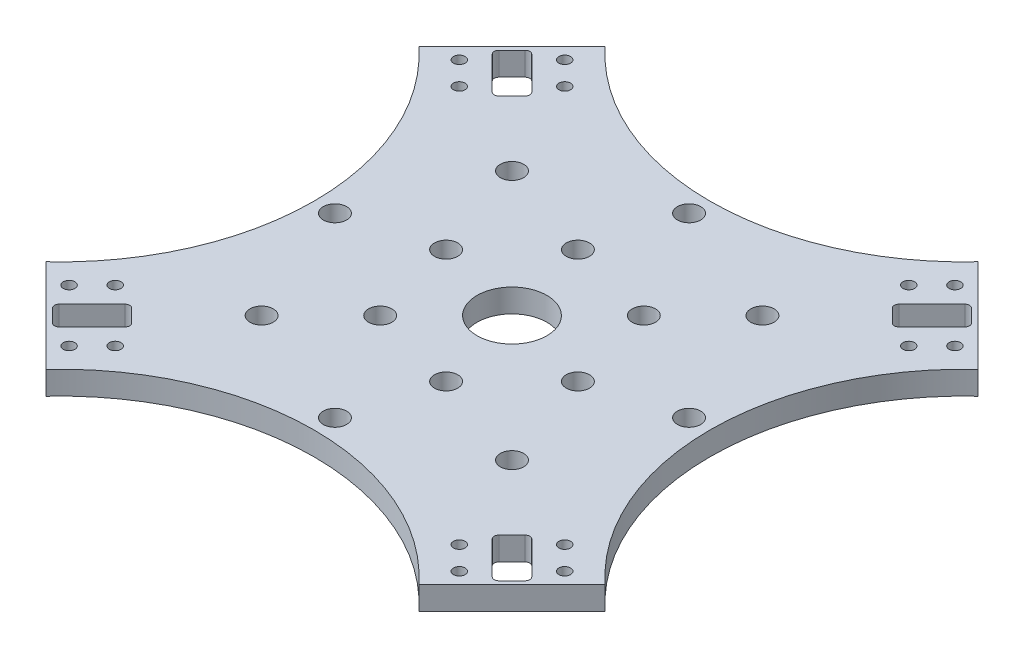
SolidWorks part; units mm, degrees
ref_plane "Front Plane" through (0, 0, 0) normal (0, 0, 1) x (1, 0, 0)
ref_plane "Top Plane" through (0, 0, 0) normal (0, 1, 0) x (1, 0, 0)
ref_plane "Right Plane" through (0, 0, 0) normal (1, 0, 0) x (0, 0, -1)
sketch "Sketch3" plane through (0, 0, 0) normal (0, 1, 0) x (1, 0, 0)
  line L0 (-60, 40) -> (-40, 60)
  line L5 (-60, 60) -> (-50, 50) construction
  line L6 (-60, -60) -> (-50, -50) construction
  line L7 (40, 60) -> (60, 40)
  line L8 (40, -60) -> (60, -40)
  line L9 (-60, -40) -> (-40, -60)
  line L10 (50, 50) -> (60, 60) construction
  line L11 (50, -50) -> (60, -60) construction
  arc A0 (-40, 60) -> (40, 60) centre (0, 96.9643) ccw
  arc A1 (-40, -60) -> (40, -60) centre (0, -96.9643) cw
  arc A2 (-60, -40) -> (-60, 40) centre (-96.9643, 0) ccw
  arc A3 (60, -40) -> (60, 40) centre (96.9643, 0) cw
  point P0 (0, 0)
  point P18 (0, 42.5)
  point P19 (-42.5, 0)
  point P20 (0, -42.5)
  point P21 (42.5, 0)
  dimension "D1" = 120
  dimension "D2" = 120
  dimension "D3" = 17.5
  dimension "D4" = 2.5
  dimension "D5" = 17.5
  dimension "D6" = 17.5
extrude "Boss-Extrude1" add sketch "Sketch3" along normal blind 5
ref_plane "Plane1" through (0, 5, 0) normal (0, 1, 0) x (1, 0, 0)
sketch "Sketch7" plane through (0, 5, 0) normal (0, 1, 0) x (1, 0, 0)
  line L0 (-50, 50) -> (50, -50)
  line L1 (-40, 60) -> (-60, 40) construction
  line L2 (40, -60) -> (60, -40) construction
  line L3 (50, 50) -> (-50, -50)
  line L4 (60, 40) -> (40, 60) construction
  line L5 (-60, -40) -> (-40, -60) construction
  line L6 (47.8787, 50.7071) -> (50.7071, 47.8787)
  line L7 (50.7071, 46.4645) -> (43.636, 39.3934)
  line L8 (42.2218, 39.3934) -> (39.3934, 42.2218)
  line L9 (46.4645, 50.7071) -> (39.3934, 43.636)
  line L10 (39.3934, -42.2218) -> (42.2218, -39.3934)
  line L11 (50.7071, -46.4645) -> (43.636, -39.3934)
  line L12 (50.7071, -47.8787) -> (47.8787, -50.7071)
  line L13 (46.4645, -50.7071) -> (39.3934, -43.636)
  line L14 (-42.2218, -39.3934) -> (-39.3934, -42.2218)
  line L15 (-46.4645, -50.7071) -> (-39.3934, -43.636)
  line L16 (-47.8787, -50.7071) -> (-50.7071, -47.8787)
  line L17 (-50.7071, -46.4645) -> (-43.636, -39.3934)
  line L18 (-39.3934, 42.2218) -> (-42.2218, 39.3934)
  line L19 (-50.7071, 46.4645) -> (-43.636, 39.3934)
  line L20 (-50.7071, 47.8787) -> (-47.8787, 50.7071)
  line L21 (-46.4645, 50.7071) -> (-39.3934, 43.636)
  arc A0 (43.636, 39.3934) -> (42.2218, 39.3934) centre (42.9289, 40.1005) cw
  arc A1 (50.7071, 47.8787) -> (50.7071, 46.4645) centre (50, 47.1716) cw
  arc A2 (39.3934, 43.636) -> (39.3934, 42.2218) centre (40.1005, 42.9289) ccw
  arc A3 (47.8787, 50.7071) -> (46.4645, 50.7071) centre (47.1716, 50) ccw
  arc A4 (43.636, -39.3934) -> (42.2218, -39.3934) centre (42.9289, -40.1005) ccw
  arc A5 (50.7071, -47.8787) -> (50.7071, -46.4645) centre (50, -47.1716) ccw
  arc A6 (47.8787, -50.7071) -> (46.4645, -50.7071) centre (47.1716, -50) cw
  arc A7 (39.3934, -43.636) -> (39.3934, -42.2218) centre (40.1005, -42.9289) cw
  arc A8 (-39.3934, -43.636) -> (-39.3934, -42.2218) centre (-40.1005, -42.9289) ccw
  arc A9 (-47.8787, -50.7071) -> (-46.4645, -50.7071) centre (-47.1716, -50) ccw
  arc A10 (-50.7071, -47.8787) -> (-50.7071, -46.4645) centre (-50, -47.1716) cw
  arc A11 (-43.636, -39.3934) -> (-42.2218, -39.3934) centre (-42.9289, -40.1005) cw
  arc A12 (-43.636, 39.3934) -> (-42.2218, 39.3934) centre (-42.9289, 40.1005) ccw
  arc A13 (-50.7071, 47.8787) -> (-50.7071, 46.4645) centre (-50, 47.1716) ccw
  arc A14 (-47.8787, 50.7071) -> (-46.4645, 50.7071) centre (-47.1716, 50) cw
  arc A15 (-39.3934, 43.636) -> (-39.3934, 42.2218) centre (-40.1005, 42.9289) cw
  circle A16 centre (-41.8683, 53.182) radius 1.25
  circle A17 centre (-36.9185, 48.2322) radius 1.25
  circle A18 centre (-48.2322, 36.9185) radius 1.25
  circle A19 centre (-53.182, 41.8683) radius 1.25
  circle A20 centre (41.8683, 53.182) radius 1.25
  circle A21 centre (36.9185, 48.2322) radius 1.25
  circle A22 centre (48.2322, 36.9185) radius 1.25
  circle A23 centre (53.182, 41.8683) radius 1.25
  circle A24 centre (53.182, -41.8683) radius 1.25
  circle A25 centre (48.2322, -36.9185) radius 1.25
  circle A26 centre (36.9185, -48.2322) radius 1.25
  circle A27 centre (41.8683, -53.182) radius 1.25
  circle A28 centre (-41.8683, -53.182) radius 1.25
  circle A29 centre (-36.9185, -48.2322) radius 1.25
  circle A30 centre (-48.2322, -36.9185) radius 1.25
  circle A31 centre (-53.182, -41.8683) radius 1.25
  point P18 (42.9289, 38.6863)
  point P21 (51.4142, 47.1716)
  point P23 (40.8076, 40.8076)
  point P28 (49.2929, 49.2929)
  point P67 (0, 0)
  point P80 (0, 0)
  point P89 (0, 0)
  point P98 (0, 0)
  point P104 (0, 0)
  dimension "D4" = 1
  dimension "D6" = 2.5
  dimension "D7" = 2.5
  dimension "D1" = 12
  dimension "D2" = 13
  dimension "D3" = 3
  dimension "D8" = 2.5
  dimension "D9" = 5
  dimension "D10" = 2.5
  dimension "D11" = 5
  dimension "D13" = 3
  dimension "D14" = 3
  dimension "D5" = 4
  dimension "D12" = 4
extrude "Cut-Extrude5" cut sketch "Sketch7" against normal blind 5 contours A15 L21 A14 L20 L0 L18 | L20 A13 L19 A12 L18 L0 | A19 | A18 | A16 | A17 | L16 A9 L15 A8 L14 L3 | A11 L17 A10 L16 L3 L14 | A31 | A30 | A28 | A7 L13 A6 L12 L0 L10 | L12 A5 L11 A4 L10 L0 | A24 | L6 A3 L9 A2 L8 L3 | A1 L6 L3 L8 A0 L7 | A20 | A21 | A23 | A22 | A29 | A25 | A27 | A26
sketch "Sketch9" plane through (0, 5, 0) normal (0, 1, 0) x (1, 0, 0)
  circle A0 centre (0, 0) radius 7.5
  circle A1 centre (26.8701, 26.8701) radius 2.5
  circle A2 centre (38, 0) radius 2.5
  circle A3 centre (26.8701, -26.8701) radius 2.5
  circle A4 centre (0, -38) radius 2.5
  circle A5 centre (-26.8701, -26.8701) radius 2.5
  circle A6 centre (-38, 0) radius 2.5
  circle A7 centre (-26.8701, 26.8701) radius 2.5
  circle A8 centre (0, 38) radius 2.5
  circle A9 centre (14.1421, 14.1421) radius 2.5
  circle A10 centre (19.3185, -5.1764) radius 2.5
  circle A11 centre (5.1764, -19.3185) radius 2.5
  circle A12 centre (-14.1421, -14.1421) radius 2.5
  circle A13 centre (-19.3185, 5.1764) radius 2.5
  circle A14 centre (-5.1764, 19.3185) radius 2.5
  point P34 (0, 0)
  point P46 (0, 0)
  dimension "D1" = 15
  dimension "D2" = 5
  dimension "D5" = 5
  dimension "D3" = 38
  dimension "D6" = 20
  dimension "D4" = 8
  dimension "D7" = 6
extrude "Cut-Extrude11" cut sketch "Sketch9" against normal blind 5
